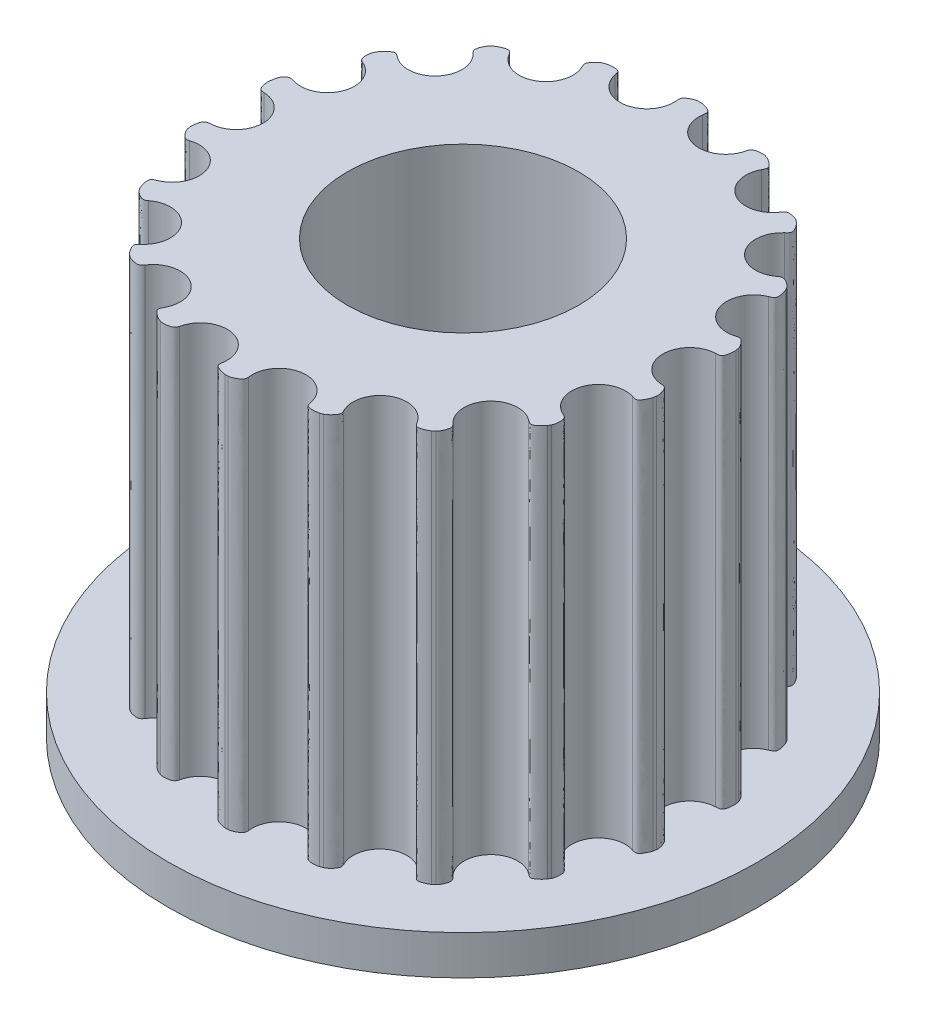
SolidWorks part; units mm, degrees
ref_plane "Front Plane" through (0, 0, 0) normal (0, 0, 1) x (1, 0, 0)
ref_plane "Top Plane" through (0, 0, 0) normal (0, 1, 0) x (1, 0, 0)
ref_plane "Right Plane" through (0, 0, 0) normal (1, 0, 0) x (0, 0, -1)
sketch "Sketch2" plane through (0, 0, 0) normal (0, 1, 0) x (1, 0, 0)
  line L0 (-5.0885, 0.254) -> (4.6531, 0.254) construction
  line L1 (0, 0) -> (-5.774, 0) construction
  line L2 (-5.2355, 2.9779) -> (-5.1967, 3.0451)
  line L3 (-3.9012, 4.589) -> (-3.8418, 4.6388)
  line L4 (-2.0964, 5.6465) -> (-2.0236, 5.673)
  line L5 (-0.0388, 6.023) -> (0.0388, 6.023)
  line L6 (2.0236, 5.673) -> (2.0964, 5.6465)
  line L7 (3.8418, 4.6388) -> (3.9012, 4.589)
  line L8 (5.1967, 3.0451) -> (5.2355, 2.9779)
  line L9 (5.9248, 1.0841) -> (5.9382, 1.0077)
  line L10 (5.9382, -1.0077) -> (5.9248, -1.0841)
  line L11 (5.2355, -2.9779) -> (5.1967, -3.0451)
  line L12 (3.9012, -4.589) -> (3.8418, -4.6388)
  line L13 (2.0964, -5.6465) -> (2.0236, -5.673)
  line L14 (0.0388, -6.023) -> (-0.0388, -6.023)
  line L15 (-2.0236, -5.673) -> (-2.0964, -5.6465)
  line L16 (-3.8418, -4.6388) -> (-3.9012, -4.589)
  line L17 (-5.1967, -3.0451) -> (-5.2355, -2.9779)
  line L18 (-5.9248, -1.0841) -> (-5.9382, -1.0077)
  line L19 (-5.9382, 1.0077) -> (-5.9248, 1.0841)
  arc A1 (-5.7474, 0.6847) -> (-5.7474, -0.6847) centre (-5.774, 0) cw
  circle A2 centre (0, 0) radius 6.0231 construction
  arc A3 (-5.1666, 2.6091) -> (-5.6349, 1.3223) centre (-5.4258, 1.9748) cw
  arc A4 (-3.9626, 4.2188) -> (-4.8429, 3.1698) centre (-4.4231, 3.7114) cw
  arc A5 (-2.2807, 5.3197) -> (-3.4667, 4.635) centre (-2.887, 5.0004) cw
  arc A6 (-0.3237, 5.7789) -> (-1.6723, 5.5411) centre (-1.0026, 5.6863) cw
  arc A7 (1.6723, 5.5411) -> (0.3237, 5.7789) centre (1.0026, 5.6863) cw
  arc A8 (3.4667, 4.635) -> (2.2807, 5.3197) centre (2.887, 5.0004) cw
  arc A9 (4.8429, 3.1698) -> (3.9626, 4.2188) centre (4.4231, 3.7114) cw
  arc A10 (5.6349, 1.3223) -> (5.1666, 2.6091) centre (5.4258, 1.9748) cw
  arc A11 (5.7474, -0.6847) -> (5.7474, 0.6847) centre (5.774, 0) cw
  arc A12 (5.1666, -2.6091) -> (5.6349, -1.3223) centre (5.4258, -1.9748) cw
  arc A13 (3.9626, -4.2188) -> (4.8429, -3.1698) centre (4.4231, -3.7114) cw
  arc A14 (2.2807, -5.3197) -> (3.4667, -4.635) centre (2.887, -5.0004) cw
  arc A15 (0.3237, -5.7789) -> (1.6723, -5.5411) centre (1.0026, -5.6863) cw
  arc A16 (-1.6723, -5.5411) -> (-0.3237, -5.7789) centre (-1.0026, -5.6863) cw
  arc A17 (-3.4667, -4.635) -> (-2.2807, -5.3197) centre (-2.887, -5.0004) cw
  arc A18 (-4.8429, -3.1698) -> (-3.9626, -4.2188) centre (-4.4231, -3.7114) cw
  arc A19 (-5.6349, -1.3223) -> (-5.1666, -2.6091) centre (-5.4258, -1.9748) cw
  circle A20 centre (0, 0) radius 5.0887 construction
  circle A21 centre (0, 0) radius 5.788 construction
  spline S0 degree 3 poles (-5.7474, 0.6847) (-5.8371, 0.6882) (-5.9207, 0.7551) (-5.9459, 0.9623) (-5.9382, 1.0077) knots 0 0 0 0 0.389029 1 1 1 1
  spline S1 degree 3 poles (-5.7474, -0.6847) (-5.8371, -0.6882) (-5.9207, -0.7551) (-5.9459, -0.9623) (-5.9382, -1.0077) knots 0 0 0 0 0.389029 1 1 1 1
  spline S2 degree 2 poles (-5.6349, 1.3223) (-5.8782, 1.4003) (-5.9248, 1.0841) knots 0 0 0 1 1 1
  spline S3 degree 3 poles (-5.1666, 2.6091) (-5.2495, 2.6434) (-5.2847, 2.7802) (-5.2584, 2.9381) (-5.2355, 2.9779) knots 0 0 0 0 0.389029 1 1 1 1
  spline S4 degree 3 poles (-4.8429, 3.1698) (-4.9136, 3.2251) (-4.9967, 3.2703) (-5.1733, 3.0847) (-5.1967, 3.0451) knots 0 0 0 0 0.389029 1 1 1 1
  spline S5 degree 3 poles (-3.9626, 4.2188) (-4.0288, 4.2794) (-4.0151, 4.4201) (-3.9364, 4.5594) (-3.9012, 4.589) knots 0 0 0 0 0.389029 1 1 1 1
  spline S6 degree 3 poles (-3.4667, 4.635) (-3.5142, 4.7111) (-3.5769, 4.7821) (-3.8063, 4.668) (-3.8418, 4.6388) knots 0 0 0 0 0.389029 1 1 1 1
  spline S7 degree 3 poles (-2.2807, 5.3197) (-2.3222, 5.3993) (-2.2612, 5.5268) (-2.1396, 5.6307) (-2.0964, 5.6465) knots 0 0 0 0 0.389029 1 1 1 1
  spline S8 degree 3 poles (-1.6723, 5.5411) (-1.691, 5.6289) (-1.7256, 5.717) (-1.9802, 5.6883) (-2.0236, 5.673) knots 0 0 0 0 0.389029 1 1 1 1
  spline S9 degree 3 poles (-0.3237, 5.7789) (-0.3355, 5.8679) (-0.2346, 5.9668) (-0.0847, 6.0229) (-0.0388, 6.023) knots 0 0 0 0 0.389029 1 1 1 1
  spline S10 degree 3 poles (0.3237, 5.7789) (0.3362, 5.8678) (0.3338, 5.9624) (0.0847, 6.0226) (0.0388, 6.023) knots 0 0 0 0 0.389029 1 1 1 1
  spline S11 degree 3 poles (1.6723, 5.5411) (1.6917, 5.6288) (1.8203, 5.6872) (1.9804, 5.6887) (2.0236, 5.673) knots 0 0 0 0 0.389029 1 1 1 1
  spline S12 degree 3 poles (2.2807, 5.3197) (2.3228, 5.3989) (2.353, 5.4887) (2.1395, 5.6304) (2.0964, 5.6465) knots 0 0 0 0 0.389029 1 1 1 1
  spline S13 degree 3 poles (3.4667, 4.635) (3.5148, 4.7107) (3.6557, 4.7217) (3.8066, 4.6683) (3.8418, 4.6388) knots 0 0 0 0 0.389029 1 1 1 1
  spline S14 degree 3 poles (3.9626, 4.2188) (4.0293, 4.2789) (4.0883, 4.3529) (3.9361, 4.5591) (3.9012, 4.589) knots 0 0 0 0 0.389029 1 1 1 1
  spline S15 degree 3 poles (4.8429, 3.1698) (4.914, 3.2245) (5.0501, 3.1866) (5.1737, 3.0848) (5.1967, 3.0451) knots 0 0 0 0 0.389029 1 1 1 1
  spline S16 degree 3 poles (5.1666, 2.6091) (5.2498, 2.6427) (5.3305, 2.6921) (5.2581, 2.9379) (5.2355, 2.9779) knots 0 0 0 0 0.389029 1 1 1 1
  spline S17 degree 3 poles (5.6349, 1.3223) (5.7205, 1.3493) (5.8355, 1.2672) (5.9167, 1.1293) (5.9248, 1.0841) knots 0 0 0 0 0.389029 1 1 1 1
  spline S18 degree 3 poles (5.7474, 0.6847) (5.837, 0.6878) (5.9298, 0.7066) (5.9458, 0.9624) (5.9382, 1.0077) knots 0 0 0 0 0.389029 1 1 1 1
  spline S19 degree 3 poles (5.7474, -0.6847) (5.837, -0.6886) (5.9169, -0.8051) (5.9462, -0.9624) (5.9382, -1.0077) knots 0 0 0 0 0.389029 1 1 1 1
  spline S20 degree 3 poles (5.6349, -1.3223) (5.7203, -1.35) (5.8139, -1.3641) (5.9164, -1.1292) (5.9248, -1.0841) knots 0 0 0 0 0.389029 1 1 1 1
  spline S21 degree 3 poles (5.1666, -2.6091) (5.2495, -2.6434) (5.2847, -2.7802) (5.2584, -2.9381) (5.2355, -2.9779) knots 0 0 0 0 0.389029 1 1 1 1
  spline S22 degree 3 poles (4.8429, -3.1698) (4.9136, -3.2251) (4.9967, -3.2703) (5.1733, -3.0847) (5.1967, -3.0451) knots 0 0 0 0 0.389029 1 1 1 1
  spline S23 degree 3 poles (3.9626, -4.2188) (4.0288, -4.2794) (4.0151, -4.4201) (3.9364, -4.5594) (3.9012, -4.589) knots 0 0 0 0 0.389029 1 1 1 1
  spline S24 degree 3 poles (3.4667, -4.635) (3.5142, -4.7111) (3.5769, -4.7821) (3.8063, -4.668) (3.8418, -4.6388) knots 0 0 0 0 0.389029 1 1 1 1
  spline S25 degree 3 poles (2.2807, -5.3197) (2.3222, -5.3993) (2.2612, -5.5268) (2.1396, -5.6307) (2.0964, -5.6465) knots 0 0 0 0 0.389029 1 1 1 1
  spline S26 degree 3 poles (1.6723, -5.5411) (1.691, -5.6289) (1.7256, -5.717) (1.9802, -5.6883) (2.0236, -5.673) knots 0 0 0 0 0.389029 1 1 1 1
  spline S27 degree 3 poles (0.3237, -5.7789) (0.3355, -5.8679) (0.2346, -5.9668) (0.0847, -6.0229) (0.0388, -6.023) knots 0 0 0 0 0.389029 1 1 1 1
  spline S28 degree 3 poles (-0.3237, -5.7789) (-0.3362, -5.8678) (-0.3338, -5.9624) (-0.0847, -6.0226) (-0.0388, -6.023) knots 0 0 0 0 0.389029 1 1 1 1
  spline S29 degree 3 poles (-1.6723, -5.5411) (-1.6917, -5.6288) (-1.8203, -5.6872) (-1.9804, -5.6887) (-2.0236, -5.673) knots 0 0 0 0 0.389029 1 1 1 1
  spline S30 degree 3 poles (-2.2807, -5.3197) (-2.3228, -5.3989) (-2.353, -5.4887) (-2.1395, -5.6304) (-2.0964, -5.6465) knots 0 0 0 0 0.389029 1 1 1 1
  spline S31 degree 3 poles (-3.4667, -4.635) (-3.5148, -4.7107) (-3.6557, -4.7217) (-3.8066, -4.6683) (-3.8418, -4.6388) knots 0 0 0 0 0.389029 1 1 1 1
  spline S32 degree 3 poles (-3.9626, -4.2188) (-4.0293, -4.2789) (-4.0883, -4.3529) (-3.9361, -4.5591) (-3.9012, -4.589) knots 0 0 0 0 0.389029 1 1 1 1
  spline S33 degree 3 poles (-4.8429, -3.1698) (-4.914, -3.2245) (-5.0501, -3.1866) (-5.1737, -3.0848) (-5.1967, -3.0451) knots 0 0 0 0 0.389029 1 1 1 1
  spline S34 degree 3 poles (-5.1666, -2.6091) (-5.2498, -2.6427) (-5.3305, -2.6921) (-5.2581, -2.9379) (-5.2355, -2.9779) knots 0 0 0 0 0.389029 1 1 1 1
  spline S35 degree 3 poles (-5.6349, -1.3223) (-5.7205, -1.3493) (-5.8355, -1.2672) (-5.9167, -1.1293) (-5.9248, -1.0841) knots 0 0 0 0 0.389029 1 1 1 1
  point P13 (0, 0)
  point P134 (0, 0)
  point P135 (0, 0)
  point P136 (0, 0)
  point P137 (0, 0)
  point P169 (0, 0)
  dimension "D1" = 12.0463
  dimension "D2" = 18
  dimension "D6" = 10.1775
  dimension "D7" = 11.576
  dimension "D8" = 0.6852
  dimension "D3" = 18
  dimension "D4" = 0.0775
  dimension "D5" = 0.6478
extrude "Boss-Extrude1" add sketch "Sketch2" along normal blind 11
sketch "Sketch3" plane through (0, 0, 0) normal (0, -1, 0) x (1, 0, 0)
  circle A0 centre (0, 0) radius 7.5
  dimension "D1" = 15
extrude "Boss-Extrude2" add sketch "Sketch3" against normal blind 1
sketch "Sketch4" plane through (0, 11, 0) normal (0, 1, 0) x (1, 0, 0)
  circle A0 centre (0, 0) radius 2.945
  dimension "D1" = 5.89
extrude "Cut-Extrude1" cut sketch "Sketch4" against normal through all both and the other way through all
